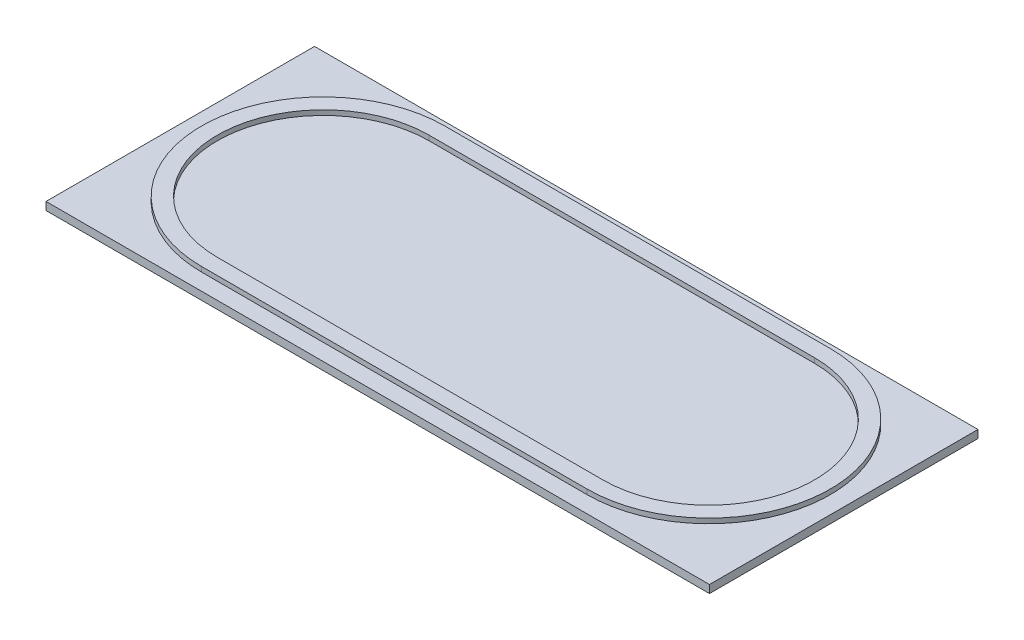
SolidWorks part; units mm, degrees
ref_plane "Front Plane" through (0, 0, 0) normal (0, 0, 1) x (1, 0, 0)
ref_plane "Top Plane" through (0, 0, 0) normal (0, 1, 0) x (1, 0, 0)
ref_plane "Right Plane" through (0, 0, 0) normal (1, 0, 0) x (0, 0, -1)
sketch "Track Sketch" plane through (0, 0, 0) normal (0, 1, 0) x (1, 0, 0)
  line L0 (-310, -195.58) -> (310, -195.58)
  line L1 (-310, -170.18) -> (310, -170.18)
  line L3 (-310, 170.18) -> (310, 170.18)
  line L5 (-310, -170.18) -> (310, 170.18) construction
  line L6 (-310, 170.18) -> (310, -170.18) construction
  line L7 (-310, 195.58) -> (310, 195.58)
  line L8 (-310, 182.88) -> (310, 182.88) construction
  line L9 (-310, -182.88) -> (310, -182.88) construction
  arc A0 (-310, 170.18) -> (-310, -170.18) centre (-310, 0) ccw
  arc A1 (310, 170.18) -> (310, -170.18) centre (310, 0) cw
  arc A2 (310, 195.58) -> (310, -195.58) centre (310, 0) cw
  arc A3 (-310, 195.58) -> (-310, -195.58) centre (-310, 0) ccw
  arc A4 (310, 182.88) -> (310, -182.88) centre (310, 0) cw construction
  arc A5 (-310, 182.88) -> (-310, -182.88) centre (-310, 0) ccw construction
  point P0 (0, 0)
  dimension "D2" = 365.76
  dimension "D1" = 620
  dimension "D3" = 25.4
  dimension "D4" = 12.7
extrude "Train Track" add sketch "Track Sketch" along normal blind 7.874 contours L0 A2 L7 A3 | L1 A1 L3 A0
sketch "Track Base Sketch" plane through (0, 0, 0) normal (0, 1, 0) x (1, 0, 0)
  line L1 (-533.4, -222.25) -> (533.4, -222.25)
  line L2 (-533.4, -222.25) -> (-533.4, 209.55)
  line L3 (-533.4, 209.55) -> (533.4, 209.55)
  line L4 (533.4, -222.25) -> (533.4, 209.55)
  line L5 (-533.4, -222.25) -> (533.4, 209.55) construction
  line L6 (-533.4, 209.55) -> (533.4, -222.25) construction
  point P0 (0, 209.55)
  dimension "D1" = 1066.8
  dimension "D2" = 431.8
  dimension "D3" = 222.25
extrude "Track Base" add sketch "Track Base Sketch" against normal blind 12.7 contours L2 L3 L4 L1
equation "\"Track_Length\"= 38"
equation "\"Track_Width\"= 14"
equation "\"Track_Gauge\"= 1"
equation "\"D3@Track Sketch\" = \"Track_Gauge\""
equation "\"Support_Width\"= 3"
equation "\"D1@Track Base Sketch\"=\"Track_Length\"+4"
equation "\"D4@Track Sketch\"=\"Track_Gauge\"/2"
equation "\"D1@Track Sketch\"=620/25.4"
